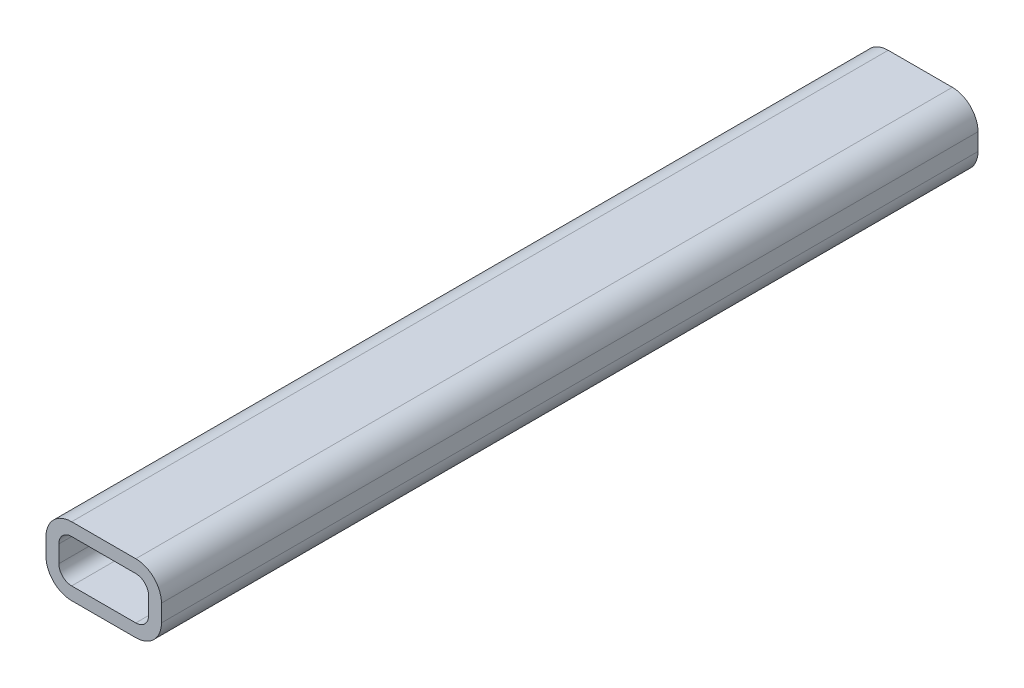
SolidWorks part; units mm, degrees
material "Natural Rubber"
ref_plane "Front Plane" through (0, 0, 0) normal (0, 0, 1) x (1, 0, 0)
ref_plane "Top Plane" through (0, 0, 0) normal (0, 1, 0) x (1, 0, 0)
ref_plane "Right Plane" through (0, 0, 0) normal (1, 0, 0) x (0, 0, -1)
sketch "Sketch1" plane through (0, 0, 0) normal (0, 0, 1) x (1, 0, 0)
  line L0 (0, 3) -> (-15, 3)
  line L1 (-21, -3) -> (-21, -7)
  line L2 (0, -13) -> (-15, -13)
  line L3 (6, -3) -> (6, -7)
  line L5 (0, 0) -> (-15, 0)
  line L6 (3, -3) -> (3, -7)
  line L7 (0, -10) -> (-15, -10)
  line L8 (-18, -3) -> (-18, -7)
  arc A0 (-15, -10) -> (-18, -7) centre (-15, -7) cw
  arc A1 (3, -7) -> (0, -10) centre (0, -7) cw
  arc A2 (0, 0) -> (3, -3) centre (0, -3) cw
  arc A3 (-15, 0) -> (-18, -3) centre (-15, -3) ccw
  arc A4 (-15, 3) -> (-21, -3) centre (-15, -3) ccw
  arc A5 (-15, -13) -> (-21, -7) centre (-15, -7) cw
  arc A6 (6, -7) -> (0, -13) centre (0, -7) cw
  arc A7 (0, 3) -> (6, -3) centre (0, -3) cw
  point P11 (-18, -10)
  point P16 (3, 0)
  point P19 (-18, 0)
  dimension "D7" = 3
  dimension "D1" = 10
  dimension "D2" = 21
  dimension "D3" = 3
extrude "Boss-Extrude1" add sketch "Sketch1" along normal blind 191
